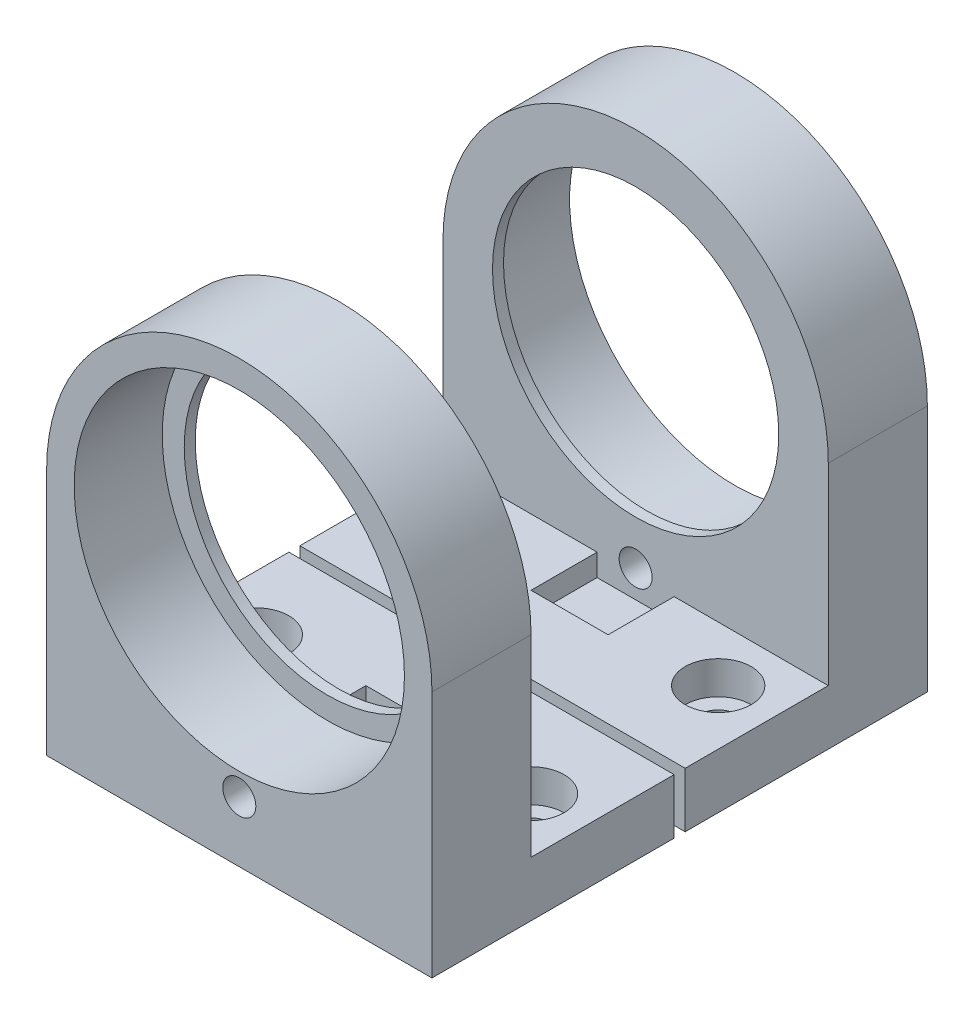
SolidWorks part; units mm, degrees
other "标注1"
sketch "草图5" plane through (-20, 40, 22.5) normal (-0.1295, 0.131, 0.9829) x (0.9907, 0.0594, 0.1226)
other "标注2"
sketch "草图13" plane through (-17.5, 0, -22.5) normal (-0.0964, -0.0078, -0.9953) x (0.9949, 0.0275, -0.0965)
other "标注3"
sketch "草图14" plane through (-17.5, 0, -22.5) normal (-0.0964, -0.0078, -0.9953) x (0.9949, 0.0275, -0.0965)
ref_plane "前视基准面" through (0, 0, 0) normal (0, 0, 1) x (1, 0, 0)
ref_plane "上视基准面" through (0, 0, 0) normal (0, 1, 0) x (1, 0, 0)
ref_plane "右视基准面" through (0, 0, 0) normal (1, 0, 0) x (0, 0, -1)
sketch "草图1" plane through (0, 0, 0) normal (1, 0, 0) x (0, 0, -1)
  line L0 (22.5, 0) -> (-22.5, 0)
  line L1 (-22.5, 0) -> (-22.5, 40)
  line L2 (-22.5, 40) -> (-13.5, 40)
  line L3 (-13.5, 40) -> (-13.5, 5)
  line L4 (-13.5, 5) -> (13.5, 5)
  line L5 (0, 5) -> (0, 0) construction
  line L6 (13.5, 40) -> (13.5, 5)
  line L7 (22.5, 40) -> (13.5, 40)
  line L8 (22.5, 0) -> (22.5, 40)
  dimension "D1" = 45
  dimension "D2" = 40
  dimension "D3" = 5
  dimension "D4" = 27
extrude "凸台-拉伸1" add sketch "草图1" along normal mid plane 35
sketch "草图2" plane through (0, 0, 22.5) normal (0, 0, 1) x (1, 0, 0)
  line L0 (17.5, 40) -> (17.5, 0) construction
  line L1 (17.5, 40) -> (-17.5, 40) construction
  line L2 (-17.5, 40) -> (-17.5, 0) construction
  line L3 (17.5, 40) -> (17.5, 10.3175)
  line L4 (17.5, 40) -> (-17.5, 40)
  line L5 (-17.5, 40) -> (-17.5, 22.5)
  arc A1 (17.5, 22.5) -> (-17.5, 22.5) centre (0, 22.5) ccw
  line M2 (-17.5, 40) -> (-17.5, 0)
  line M5 (17.5, 40) -> (-17.5, 40)
  dimension "D1" = 35
extrude "切除-拉伸1" cut sketch "草图2" against normal through all both and the other way through all contours A1 L4 M2 | A1 L3 M5
sketch "草图6" plane through (0, 5, 0) normal (0, 1, 0) x (1, 0, 0)
  line L0 (-17.5, 0) -> (17.5, 0) construction
  line L1 (-17.5, 13.5) -> (-17.5, -13.5) construction
  line L2 (17.5, 13.5) -> (17.5, -13.5) construction
  line L3 (0, 13.5) -> (0, -13.5) construction
  line L4 (17.5, 13.5) -> (-17.5, 13.5) construction
  line L5 (17.5, -13.5) -> (-17.5, -13.5) construction
  circle A0 centre (-12.5, 8.5) radius 1.55
  circle A1 centre (12.5, 8.5) radius 1.55
  circle A2 centre (12.5, -8.5) radius 1.55
  circle A3 centre (-12.5, -8.5) radius 1.55
  dimension "D1" = 3.1
  dimension "D2" = 5
  dimension "D3" = 5
extrude "切除-拉伸4" cut sketch "草图6" against normal through all
sketch "草图7" plane through (0, 0, 22.5) normal (0, 0, 1) x (1, 0, 0)
  circle A0 centre (0, 22.5) radius 15
  dimension "D1" = 30
extrude "切除-拉伸5" cut sketch "草图7" against normal blind 8
sketch "草图8" plane through (0, 0, 14.5) normal (0, 0, 1) x (1, 0, 0)
  circle A0 centre (0, 22.5) radius 13
  dimension "D1" = 26
extrude "切除-拉伸6" cut sketch "草图8" against normal blind 2
mirror "镜向1" about plane through (0, 0, 0) normal (0, 0, 1) of "切除-拉伸5", "切除-拉伸6"
sketch "草图9" plane through (0, 0, -22.5) normal (0, 0, -1) x (-1, 0, 0)
  line L0 (-17.5, 0) -> (-17.5, 22.5) construction
  circle A0 centre (0, 5.5) radius 1.5
  circle A1 centre (0, 22.5) radius 15 construction
  dimension "D1" = 17.5
  dimension "D2" = 17
extrude "切除-拉伸7" cut sketch "草图9" against normal blind 14
sketch "草图10" plane through (0, 5, 0) normal (0, 1, 0) x (1, 0, 0)
  line L0 (-1.4142, 13.5) -> (-17.5, 13.5) construction
  line L1 (-3.5, 13.5) -> (3.5, 13.5)
  line L2 (-3.5, 13.5) -> (-3.5, 7.5)
  line L3 (-3.5, 7.5) -> (3.5, 7.5)
  line L4 (3.5, 13.5) -> (3.5, 7.5)
  line L6 (17.5, 13.5) -> (17.5, -13.5) construction
  line L7 (-17.5, 13.5) -> (-17.5, -13.5) construction
  dimension "D1" = 14
  dimension "D2" = 14
extrude "切除-拉伸8" cut sketch "草图10" against normal blind 2
mirror "镜向2" about plane through (0, 0, 0) normal (0, 0, 1) of "切除-拉伸8", "切除-拉伸7"
sketch "草图15" plane through (0, 5, 0) normal (0, 1, 0) x (1, 0, 0)
  line L0 (-17.5, 0) -> (17.5, 0) construction
  line L1 (-17.5, 13.5) -> (-17.5, -13.5) construction
  line L2 (17.5, 13.5) -> (17.5, -13.5) construction
  line L4 (-17.5, 0.5) -> (17.5, 0.5)
  line L5 (-17.5, 0.5) -> (-17.5, -0.5)
  line L6 (-17.5, -0.5) -> (17.5, -0.5)
  line L7 (17.5, 0.5) -> (17.5, -0.5)
  dimension "D1" = 1
  dimension "D2" = 0.5
extrude "切除-拉伸9" cut sketch "草图15" against normal blind 10
sketch "草图16" plane through (0, 5, 0) normal (0, 1, 0) x (1, 0, 0)
  circle A0 centre (-12.5, 8.5) radius 3
  circle A1 centre (12.5, 8.5) radius 3
  circle A2 centre (12.5, -8.5) radius 3
  circle A3 centre (-12.5, -8.5) radius 3
  dimension "D1" = 6
extrude "切除-拉伸10" cut sketch "草图16" against normal blind 3
